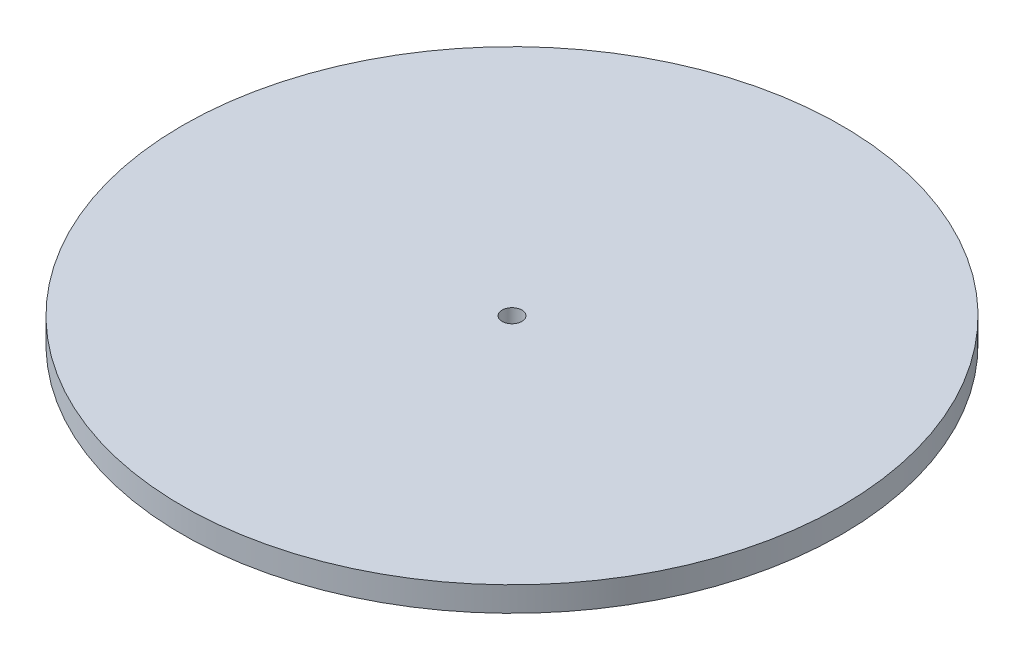
SolidWorks part; units mm, degrees
ref_plane "Front Plane" through (0, 0, 0) normal (0, 0, 1) x (1, 0, 0)
ref_plane "Top Plane" through (0, 0, 0) normal (0, 1, 0) x (1, 0, 0)
ref_plane "Right Plane" through (0, 0, 0) normal (1, 0, 0) x (0, 0, -1)
sketch "Sketch3" plane through (0, 0, 0) normal (0, 0, 1) x (1, 0, 0)
  line L0 (37, 4.4753) -> (37, 8.4753) construction
  line L1 (37, 8.4753) -> (0, 8.4753) construction
  line L2 (0, 8.4753) -> (0, 0) construction
  line L4 (1.2, 8.4753) -> (1.2, 3.4753)
  line L5 (1.2, 3.4753) -> (0, 3.4753)
  line L6 (0, 3.4753) -> (0, 0)
  line L7 (37, 4.4753) -> (40, 4.4753) construction
  line L8 (40, 4.4753) -> (40, 8.4753) construction
  line L9 (40, 8.4753) -> (1.2, 8.4753)
  line L10 (37, 4.4753) -> (37, 5.4753)
  line L11 (37, 5.4753) -> (40, 5.4753)
  line L12 (40, 5.4753) -> (40, 8.4753)
  spline S0 degree 8 poles (-3.7, 0.065) (1.8467, -0.1277) (7.3933, -0.006) (12.94, 0.5247) (18.4866, 1.3325) (24.0333, 2.2032) (29.5799, 3.1693) (35.1266, 4.1391) (40.6732, 5.1254) knots 0 0 0 0 0 0 0 0 0 1 1 1 1 1 1 1 1 1 construction
  spline S1 degree 8 poles (0, 0) (4.625, 0.0002) (9.25, 0.2368) (13.875, 0.7161) (18.5, 1.3611) (23.125, 2.0811) (27.75, 2.8593) (32.375, 3.6608) (37, 4.4753) knots 0.083384 0.083384 0.083384 0.083384 0.083384 0.083384 0.083384 0.083384 0.083384 0.91722 0.91722 0.91722 0.91722 0.91722 0.91722 0.91722 0.91722 0.91722
  dimension "D1" = 3
  dimension "D2" = 1.2
  dimension "D3" = 5
  dimension "D4" = 3
  dimension "D5" = 40
  dimension "D6" = 4.4753
  dimension "D7" = 37
  dimension "D8" = 4
revolve "Revolve4" add sketch "Sketch3" angle 360 about L2
sketch "Sketch5" plane through (0, 8.4753, 0) normal (0, 1, 0) x (1, 0, 0)
  circle A0 centre (0, 0) radius 1.2
  circle A2 centre (0, 0) radius 1.2 construction
extrude "Cut-Extrude1" cut sketch "Sketch5" against normal through all
